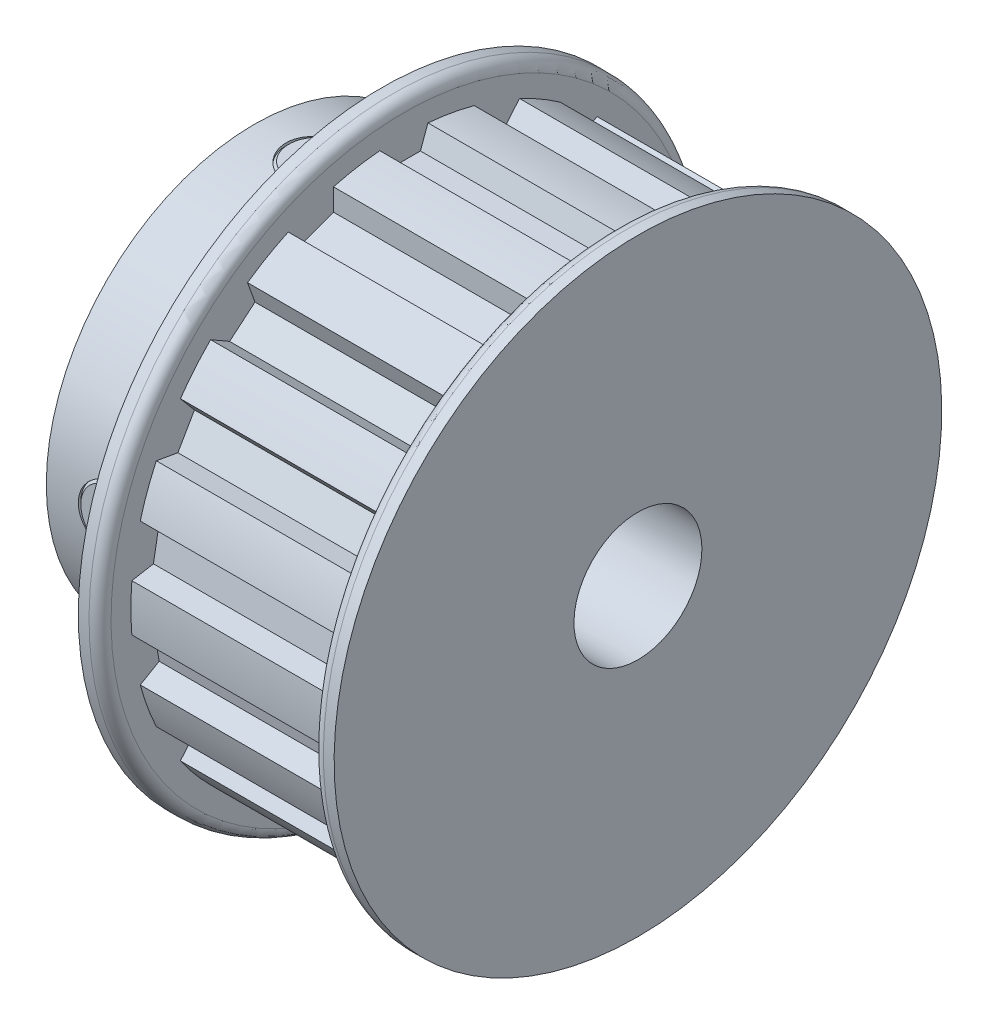
SolidWorks part; units mm, degrees
ref_plane "Front Plane" through (0, 0, 0) normal (0, 0, 1) x (1, 0, 0)
ref_plane "Top Plane" through (0, 0, 0) normal (0, 1, 0) x (1, 0, 0)
ref_plane "Right Plane" through (0, 0, 0) normal (1, 0, 0) x (0, 0, -1)
sketch "Sketch2" plane through (0, 0, 0) normal (1, 0, 0) x (0, 0, -1)
  line L3 (0, 0) -> (0, 25.0052) construction
  line L6 (0, -26.9102) -> (0, -27.2923) construction
  line L7 (-2.3241, 26.8097) -> (-1.6476, 24.9509)
  line L8 (2.3241, 26.8097) -> (1.6476, 24.9509)
  line L9 (-2.3241, 26.8097) -> (-2.3917, 26.9955)
  line L10 (2.3241, 26.8097) -> (2.3917, 26.9955)
  line L12 (-1.6476, 24.9509) -> (1.6476, 24.9509)
  line L14 (0, 26.9102) -> (0, 27.2923) construction
  line L15 (0, 0) -> (0, -3.556) construction
  circle A0 centre (0, 0) radius 27.2923 construction
  circle A1 centre (0, 0) radius 25.0052 construction
  circle A2 centre (0, 0) radius 26.9102 construction
  arc A7 (2.3917, 26.9955) -> (-2.3917, 26.9955) centre (0, 0) ccw
  point P5 (0, 27.1013)
  dimension "D1" = 40
  dimension "PD" = 54.5846
  dimension "D2" = 53.8204
  dimension "bt" = 4.6482
  dimension "hs" = 3.556
  dimension "ht" = 1.905
sketch "Sketch1" plane through (0, 0, 0) normal (0, 0, 1) x (1, 0, 0)
  line L0 (-19.05, 0) -> (19.05, 0) construction
  line L1 (-19.05, 6.35) -> (19.05, 6.35)
  line L2 (-19.05, 6.35) -> (-19.05, 20.6375)
  line L3 (-6.35, 30.1625) -> (-5.2832, 30.1625)
  line L4 (-4.191, 27.2923) -> (-4.191, 29.0703)
  line L5 (-4.191, 30.8483) -> (-4.191, 27.2923) construction
  line L6 (-4.191, 27.2923) -> (16.891, 27.2923)
  line L7 (16.891, 27.2923) -> (16.891, 29.0703)
  line L8 (16.891, 27.2923) -> (19.05, 27.2923) construction
  line L9 (17.9832, 30.1625) -> (19.05, 30.1625)
  line L10 (19.05, 30.1625) -> (19.05, 6.35)
  line L11 (-6.35, 20.6375) -> (19.05, 20.6375) construction
  line L12 (-12.7, 20.6375) -> (-12.7, 6.35) construction
  line L13 (-6.35, 30.1625) -> (-6.35, 20.6375)
  line L14 (-6.35, 20.6375) -> (-19.05, 20.6375)
  line L15 (6.35, 20.6375) -> (6.35, 27.2923) construction
  arc A0 (16.891, 29.0703) -> (17.9832, 30.1625) centre (17.9832, 29.0703) cw
  arc A1 (-4.191, 29.0703) -> (-5.2832, 30.1625) centre (-5.2832, 29.0703) ccw
  dimension "Bore Size" = 12.7
  dimension "D2" = 54.5846
  dimension "Overall Width" = 38.1
  dimension "Inside Width" = 21.082
  dimension "Outside Width" = 25.4
  dimension "Hub Dia" = 41.275
  dimension "OD" = 60.325
  dimension "D3" = 3.556
  dimension "D4" = 1.778
revolve "Revolve1" add sketch "Sketch1" angle 360 about L0
sketch "Sketch4" plane through (-4.191, 0, 0) normal (1, 0, 0) x (0, 0, -1)
  circle A0 centre (0, 0) radius 27.1013
  circle A2 centre (0, 0) radius 27.2923
  circle A3 centre (0, 0) radius 27.2923 construction
extrude "Cut-Extrude2" cut sketch "Sketch4" along normal up to surface (21.082 mm away) up to face at (16.891, -27.2923, 0)
sketch "Sketch3" plane through (-4.191, 0, 0) normal (1, 0, 0) x (0, 0, -1)
  line L2 (-2.3241, 26.8097) -> (-1.6476, 24.9509) construction
  line L3 (-1.6476, 24.9509) -> (1.6476, 24.9509) construction
  line L4 (2.3241, 26.8097) -> (1.6476, 24.9509) construction
  line L5 (-2.3917, 26.9955) -> (-1.6476, 24.9509)
  line L6 (-1.6476, 24.9509) -> (1.6476, 24.9509)
  line L7 (2.3917, 26.9955) -> (1.6476, 24.9509)
  arc A1 (2.3917, 26.9955) -> (-2.3917, 26.9955) centre (0, 0) ccw construction
  arc A2 (2.3917, 26.9955) -> (-2.3917, 26.9955) centre (0, 0) ccw
extrude "Cut-Extrude1" cut sketch "Sketch3" along normal up to surface (21.082 mm away)
pattern_circular "CirPattern1" count 18 over 360 about axis through (0, 0, 0) along (1, 0, 0) of "Cut-Extrude1"
sketch "Sketch5" plane through (0, 0, 0) normal (0, 0, 1) x (1, 0, 0)
  line L1 (16.891, 29.0703) -> (16.891, -29.0703) construction
  point P0 (16.891, 0)
sketch "Sketch6" plane through (0, 0, 0) normal (0, 1, 0) x (1, 0, 0)
  line L0 (-19.05, 0) -> (-15.875, 0) construction
  line L1 (-19.05, 30.1625) -> (-19.05, -30.1625) construction
  line L2 (-6.35, 0) -> (-9.525, 0) construction
  line L4 (-6.35, 30.1625) -> (-6.35, -30.1625) construction
  circle A0 centre (-12.7, 0) radius 3.175
  dimension "D1" = 6.35
extrude "Cut-Extrude3" cut sketch "Sketch6" along normal through all
sketch "Sketch7" plane through (0, 0, 0) normal (0, 0, 1) x (1, 0, 0)
  line L0 (-15.621, 20.6375) -> (-12.7, 20.6375)
  line L1 (-15.875, 20.3835) -> (-15.875, 6.985)
  line L2 (-15.875, 6.985) -> (-15.621, 6.731)
  line L3 (-15.621, 6.731) -> (-12.7, 6.731)
  line L4 (-12.7, 6.731) -> (-12.7, 20.6375) construction
  line L5 (-6.35, 20.6375) -> (-19.05, 20.6375) construction
  line L6 (-15.875, 20.3835) -> (-15.621, 20.6375)
  line L8 (-12.7, 20.6375) -> (-12.7, 6.731)
  point P0 (-15.875, 20.6375)
  point P4 (-15.875, 6.731)
  dimension "D1" = 6.35
  dimension "D4" = 0.254
  dimension "D5" = 0.254
  dimension "D2" = 0.381
revolve "Revolve2" add sketch "Sketch7" angle 360 about L4
sketch "Sketch8" plane through (0, 20.6375, 0) normal (0, 1, 0) x (1, 0, 0)
  line L1 (-12.7, 1.8331) -> (-14.2875, 0.9165)
  line L2 (-14.2875, 0.9165) -> (-14.2875, -0.9165)
  line L3 (-14.2875, -0.9165) -> (-12.7, -1.8331)
  line L4 (-12.7, -1.8331) -> (-11.1125, -0.9165)
  line L5 (-11.1125, -0.9165) -> (-11.1125, 0.9165)
  line L6 (-11.1125, 0.9165) -> (-12.7, 1.8331)
  circle A0 centre (-12.7, 0) radius 1.5875 construction
  dimension "D1" = 3.175
extrude "Cut-Extrude4" cut sketch "Sketch8" against normal blind 2.032
pattern_circular "CirPattern2" count 2 over 90 about axis through (-19.05, 0, 0) along (-1, 0, 0) of "Cut-Extrude3"
pattern_circular "CirPattern3" count 2 over 90 about axis through (0, 0, 0) along (1, 0, 0) of bodies 107
equation "\"D2@Sketch1\" = \"PD@Sketch2\""
equation "\"D3@Sketch1\" = \"hs@Sketch2\""
equation "\"D4@Sketch1\" = \"D3@Sketch1\"/2"
equation "\"D2@Sketch2\" = \"PD@Sketch2\"*.986"
